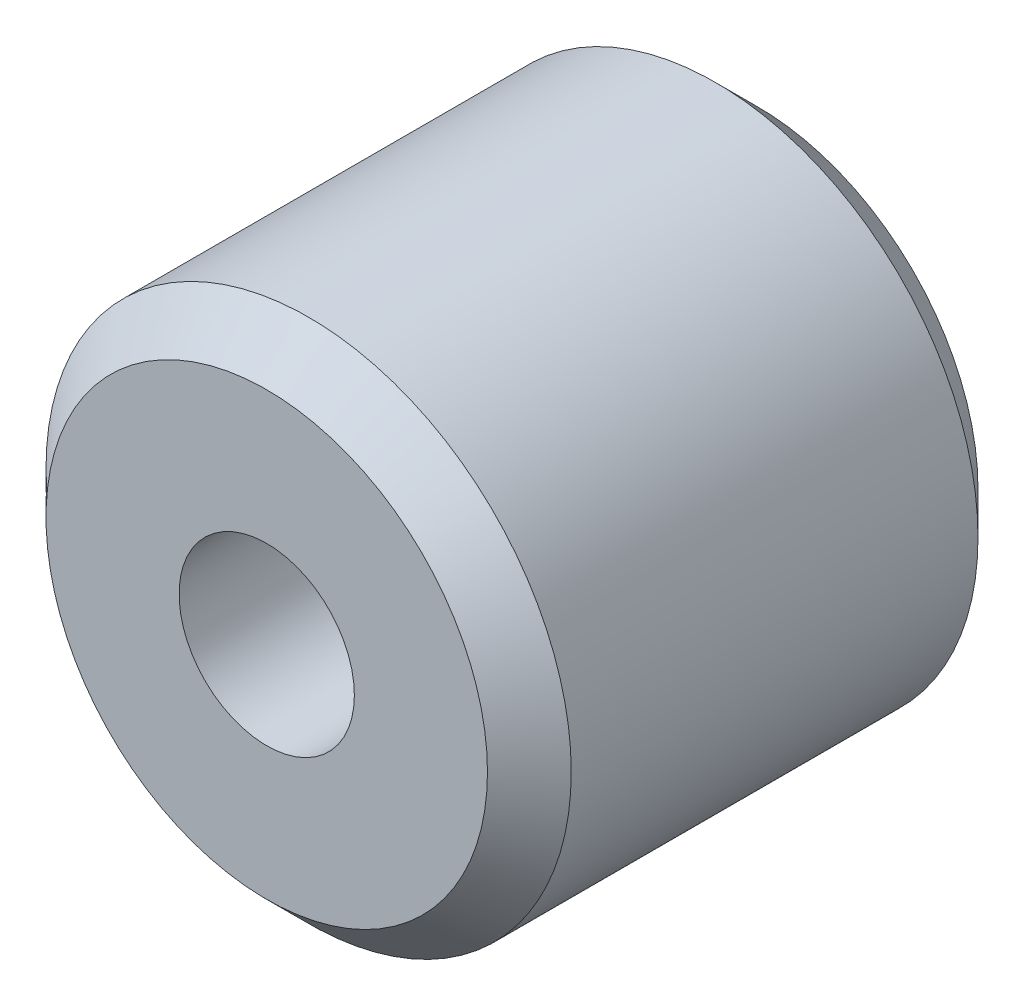
SolidWorks part; units mm, degrees
ref_plane "Front Plane" through (0, 0, 0) normal (0, 0, 1) x (1, 0, 0)
ref_plane "Top Plane" through (0, 0, 0) normal (0, 1, 0) x (1, 0, 0)
ref_plane "Right Plane" through (0, 0, 0) normal (1, 0, 0) x (0, 0, -1)
sketch "Sketch1" plane through (0, 0, 0) normal (0, 0, 1) x (1, 0, 0)
  circle A0 centre (0, 0) radius 1.59
  circle A1 centre (0, 0) radius 4.765
  dimension "D1" = 9.53
  dimension "D2" = 3.18
extrude "Boss-Extrude1" add sketch "Sketch1" along normal mid plane 8.9
chamfer "Chamfer1" distance 0.76 angle 45 2 edges at (4.765, 0, 4.45) (4.765, 0, -4.45)
